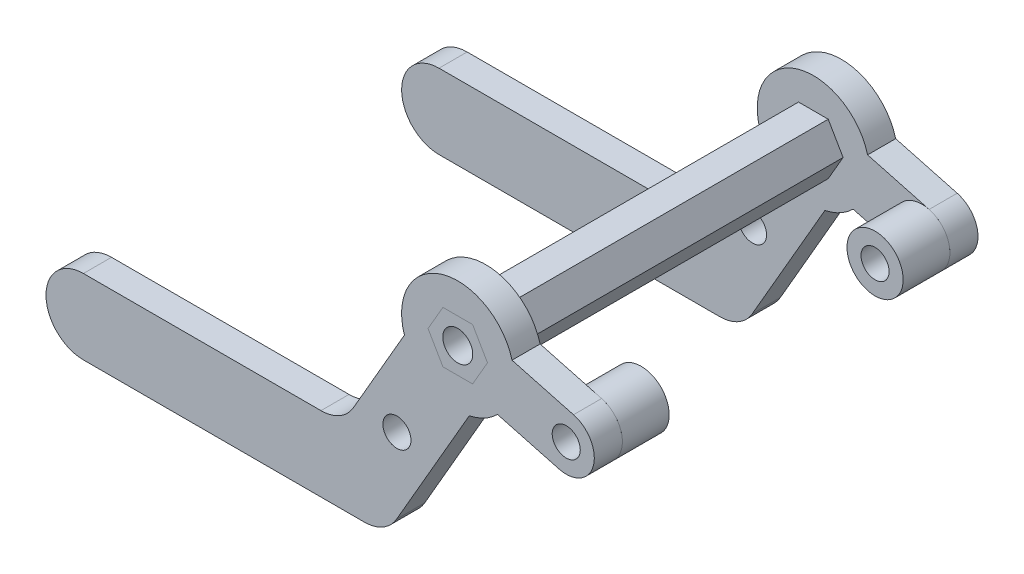
SolidWorks part; units mm, degrees
ref_plane "正面" through (0, 0, 0) normal (0, 0, 1) x (1, 0, 0)
ref_plane "平面" through (0, 0, 0) normal (0, 1, 0) x (1, 0, 0)
ref_plane "右側面" through (0, 0, 0) normal (1, 0, 0) x (0, 0, -1)
sketch "ｽｹｯﾁ1" plane through (0, 0, 0) normal (0, 0, 1) x (1, 0, 0)
  line L0 (0, 0) -> (-10, -17.3205) construction
  line L1 (-1.5877, -2.75) -> (1.5877, -2.75)
  line L2 (1.5877, -2.75) -> (3.1754, 0)
  line L3 (3.1754, 0) -> (1.5877, 2.75)
  line L4 (1.5877, 2.75) -> (-1.5877, 2.75)
  line L5 (-1.5877, 2.75) -> (-3.1754, 0)
  line L6 (-3.1754, 0) -> (-1.5877, -2.75)
  line L7 (-10, -17.3205) -> (-40, -17.3205) construction
  line L8 (-5.7002, -1.873) -> (-11.1547, -11.3205)
  line L9 (-14.6188, -13.3205) -> (-40, -13.3205)
  line L10 (1.228, -5.873) -> (-6.5359, -19.3205)
  line L11 (-10, -21.3205) -> (-40, -21.3205)
  line L12 (-3.4641, 2) -> (-12.3094, -13.3205) construction
  line L13 (-12.3094, -13.3205) -> (-40, -13.3205) construction
  line L14 (3.4641, -2) -> (-7.6906, -21.3205) construction
  line L15 (-7.6906, -21.3205) -> (-40, -21.3205) construction
  line L16 (5.7956, 1.5529) -> (12.3676, -0.2081)
  line L18 (10.8147, -6.0036) -> (4.2426, -4.2426)
  line L23 (11.5911, -3.1058) -> (0, 0) construction
  circle A0 centre (0, 0) radius 2.75 construction
  arc A2 (-40, -13.3205) -> (-40, -21.3205) centre (-40, -17.3205) ccw
  arc A3 (-11.1547, -11.3205) -> (-14.6188, -13.3205) centre (-14.6188, -9.3205) cw
  arc A4 (-6.5359, -19.3205) -> (-10, -21.3205) centre (-10, -17.3205) cw
  arc A5 (5.7956, 1.5529) -> (-5.7002, -1.873) centre (0, 0) ccw
  arc A6 (12.3676, -0.2081) -> (10.8147, -6.0036) centre (11.5911, -3.1058) cw
  arc A7 (4.2426, -4.2426) -> (5.7956, 1.5529) centre (0, 0) ccw construction
  arc A8 (1.228, -5.873) -> (4.2426, -4.2426) centre (0, 0) ccw
  arc A9 (-3, -5.1962) -> (1.228, -5.873) centre (0, 0) ccw construction
  arc A10 (-5.7002, -1.873) -> (-3, -5.1962) centre (0, 0) ccw construction
  circle A11 centre (11.5911, -3.1058) radius 1.5
  circle A12 centre (-6.5, -11.2583) radius 1.5
  dimension "D1" = 5.5
  dimension "D6" = 12
  dimension "D7" = 12
  dimension "D8" = 3
  dimension "D10" = 3
  dimension "D11" = 3
  dimension "D2" = 120
  dimension "D3" = 20
  dimension "D4" = 30
  dimension "D5" = 4
  dimension "D9" = 75
  dimension "D12" = 13
extrude "ﾎﾞｽ - 押し出し1" add sketch "ｽｹｯﾁ1" along normal mid plane 3
pattern_linear "直線ﾊﾟﾀｰﾝ1" count 2 spacing 38 along (0, 0, 1) of bodies 101
ref_plane "平面1" through (0, 0, 19) normal (0, 0, -1) x (-1, 0, 0)
sketch "ｽｹｯﾁ2" plane through (0, 0, 39.5) normal (0, 0, 1) x (1, 0, 0)
  line L7 (-1.5877, -2.75) -> (1.5877, -2.75)
  line L8 (-3.1754, 0) -> (-1.5877, -2.75)
  line L9 (-1.5877, 2.75) -> (-3.1754, 0)
  line L10 (1.5877, 2.75) -> (-1.5877, 2.75)
  line L11 (3.1754, 0) -> (1.5877, 2.75)
  line L12 (1.5877, -2.75) -> (3.1754, 0)
  line L13 (-1.5877, -2.75) -> (1.5877, -2.75)
  line L14 (-3.1754, 0) -> (-1.5877, -2.75)
  line L15 (-1.5877, 2.75) -> (-3.1754, 0)
  line L16 (1.5877, 2.75) -> (-1.5877, 2.75)
  line L17 (3.1754, 0) -> (1.5877, 2.75)
  line L18 (1.5877, -2.75) -> (3.1754, 0)
  circle A0 centre (0, 0) radius 1.6
  dimension "D2" = 3.2
  dimension "D1" = 0
extrude "ﾎﾞｽ - 押し出し2" add sketch "ｽｹｯﾁ2" against normal up to surface (41 mm away) separate body up to face at (-7.9808, -9.3821, -1.5)
sketch "ｽｹｯﾁ4" plane through (0, 0, 1.5) normal (0, 0, 1) x (1, 0, 0)
  circle A0 centre (11.5911, -3.1058) radius 3
  circle A1 centre (11.5911, -3.1058) radius 1.5 construction
  circle A2 centre (11.5911, -3.1058) radius 1.5
  dimension "D1" = 6
extrude "ﾎﾞｽ - 押し出し3" add sketch "ｽｹｯﾁ4" along normal blind 5 separate body
mirror "ﾐﾗｰ1" about plane through (0, 0, 19) normal (0, 0, -1) of bodies 104
